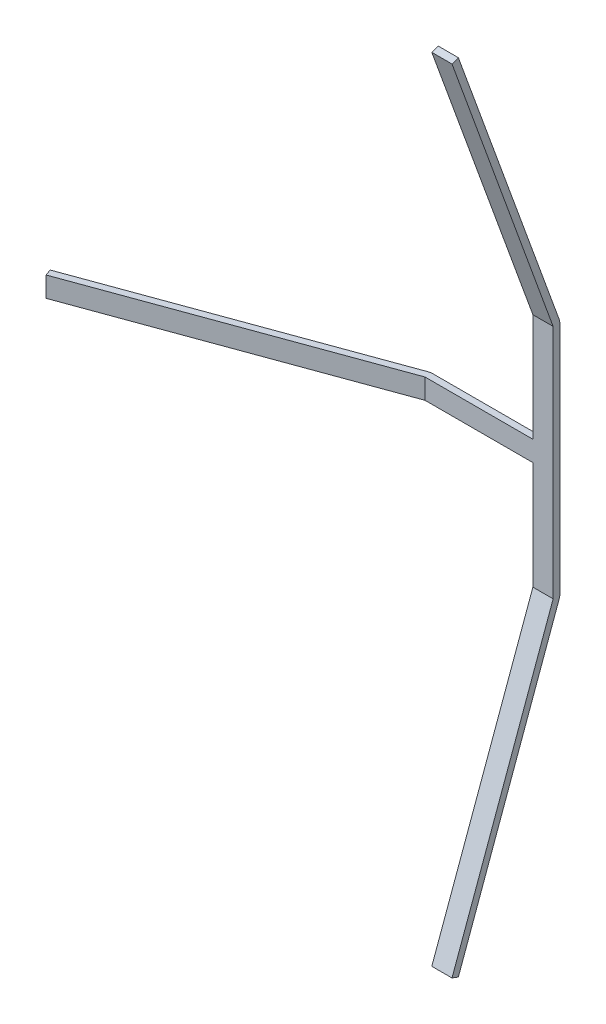
SolidWorks part; units mm, degrees
ref_plane "Front Plane" through (0, 0, 0) normal (0, 0, 1) x (1, 0, 0)
ref_plane "Top Plane" through (0, 0, 0) normal (0, 1, 0) x (1, 0, 0)
ref_plane "Right Plane" through (0, 0, 0) normal (1, 0, 0) x (0, 0, -1)
sketch "Sketch1" plane through (0, 0, 0) normal (0, 1, 0) x (1, 0, 0)
  line L0 (0, 0) -> (412.1216, 0)
  line L1 (412.1216, 0) -> (412.1216, 150)
  line L2 (412.1216, 150) -> (0, 0)
  dimension "D1" = 150
  dimension "D2" = 20
extrude "Boss-Extrude1" add sketch "Sketch1" along normal blind 350
sketch "Sketch2" plane through (412.1216, 0, 0) normal (1, 0, 0) x (0, 0, -1)
  line L4 (0, 0) -> (150, 0)
  line L5 (150, 0) -> (150, 350)
  line L6 (150, 350) -> (0, 350)
  line L7 (0, 350) -> (0, 0)
  line L8 (0, 0) -> (150, 0)
  line L9 (150, 0) -> (150, 350)
  line L10 (150, 350) -> (0, 350)
  line L11 (0, 350) -> (0, 0)
  dimension "D1" = 0
extrude "Boss-Extrude2" add sketch "Sketch2" along normal blind 350
sketch "Sketch4" plane through (762.1216, 0, 0) normal (1, 0, 0) x (0, 0, -1)
  line L0 (0, 350) -> (0, 762.1216)
  line L1 (0, 762.1216) -> (150, 350)
  line L2 (0, 350) -> (150, 350)
  line L6 (0, 350) -> (0, 0)
  line L7 (0, 0) -> (150, 0)
  line L8 (150, 0) -> (150, 350)
  line L9 (150, 350) -> (0, 350)
  line L10 (0, 350) -> (0, 0)
  line L11 (0, 0) -> (150, 0)
  line L12 (150, 0) -> (150, 350)
  line M10 (150, 350) -> (0, 350)
  dimension "D1" = 20
  dimension "D2" = 0
extrude "Boss-Extrude3" add sketch "Sketch4" against normal blind 350 contours L1 L0 M10
sketch "Sketch5" plane through (762.1216, 0, 0) normal (1, 0, 0) x (0, 0, -1)
  line L0 (0, 0) -> (0, -412.1216)
  line L1 (0, -412.1216) -> (150, 0)
  line L2 (0, 0) -> (150, 0)
  dimension "D1" = 20
extrude "Boss-Extrude4" add sketch "Sketch5" against normal blind 350
sketch "Sketch6" plane through (0, 0, 0) normal (-0.342, 0, -0.9397) x (-0.9397, 0, 0.342)
  line L0 (0, 160) -> (-438.5707, 160)
  line L1 (0, 350) -> (0, 0) construction
  line L2 (-438.5707, 350) -> (-438.5707, 0) construction
  line L3 (0, 175) -> (-124.4564, 175) construction
  line L4 (0, 190) -> (-438.5707, 190)
  line L5 (0, 190) -> (0, 160)
  line L6 (-438.5707, 190) -> (-438.5707, 160)
  dimension "D1" = 15
extrude "Cut-Extrude1" cut sketch "Sketch6" against normal blind 10
sketch "Sketch7" plane through (0, 0, -150) normal (0, 0, -1) x (-1, 0, 0)
  line L0 (-587.1216, 350) -> (-587.1216, 0) construction
  line L1 (-762.1216, 350) -> (-412.1216, 350) construction
  line L2 (-762.1216, 0) -> (-412.1216, 0) construction
  line L3 (-415.5418, 175) -> (-762.1216, 175) construction
  line L4 (-415.5418, 190) -> (-415.5418, 160) construction
  line L5 (-762.1216, 0) -> (-762.1216, 350) construction
  line L6 (-412.1216, 190) -> (-572.1216, 190)
  line L7 (-572.1216, 190) -> (-572.1216, 350)
  line L8 (-412.1216, 160) -> (-572.1216, 160)
  line L9 (-572.1216, 160) -> (-572.1216, 0)
  line L10 (-602.1216, 160) -> (-602.1216, 0)
  line L11 (-602.1216, 190) -> (-602.1216, 350)
  line L12 (-602.1216, 190) -> (-602.1216, 164.9009)
  line L13 (-602.1216, 0) -> (-572.1216, 0)
  line L14 (-602.1216, 350) -> (-572.1216, 350)
  line L15 (-412.1216, 160) -> (-412.1216, 190)
  line L16 (-602.1216, 164.9009) -> (-602.1216, 160)
  dimension "D1" = 15
extrude "Cut-Extrude2" cut sketch "Sketch7" against normal blind 10
sketch "Sketch8" plane through (0, -48.2091, -132.4533) normal (0, -0.342, -0.9397) x (-1, 0, 0)
  line L0 (-602.1216, 51.303) -> (-602.1216, -387.2676)
  line L1 (-412.1216, -387.2676) -> (-762.1216, -387.2676) construction
  line L2 (-572.1216, 51.303) -> (-572.1216, -387.2676)
  line L3 (-572.1216, -387.2676) -> (-602.1216, -387.2676)
  line L4 (-602.1216, 51.303) -> (-572.1216, 51.303)
extrude "Cut-Extrude3" cut sketch "Sketch8" against normal blind 10
sketch "Sketch9" plane through (0, 89.1513, -244.9412) normal (0, 0.342, -0.9397) x (-1, 0, 0)
  line L0 (-602.1216, 277.5894) -> (-602.1216, 716.1601)
  line L1 (-412.1216, 716.1601) -> (-762.1216, 716.1601) construction
  line L2 (-572.1216, 277.5894) -> (-572.1216, 716.1601)
  line L3 (-572.1216, 716.1601) -> (-602.1216, 716.1601)
  line L4 (-602.1216, 277.5894) -> (-572.1216, 277.5894)
extrude "Cut-Extrude4" cut sketch "Sketch9" against normal blind 10
sketch "Sketch12" plane through (0, 0, 0) normal (-0.342, 0, -0.9397) x (-0.9397, 0, 0.342)
  line L0 (0, 190) -> (-438.5707, 190) construction
  line L1 (-438.5707, 160) -> (0, 160) construction
  line L2 (0, 190) -> (-438.5707, 190)
  line L3 (-438.5707, 160) -> (0, 160)
  line L4 (0, 160) -> (0, 190)
  line L5 (-438.5707, 160) -> (-438.5707, 190)
extrude "Boss-Extrude5" add sketch "Sketch12" along normal blind 10 separate body
sketch "Sketch13" plane through (0, 0, -150) normal (0, 0, -1) x (-1, 0, 0)
  line L0 (-572.1216, 0) -> (-572.1216, 160) construction
  line L1 (-602.1216, 350) -> (-602.1216, 0) construction
  line L2 (-572.1216, 190) -> (-572.1216, 350) construction
  line L3 (-412.1216, 190) -> (-572.1216, 190) construction
  line L4 (-572.1216, 160) -> (-412.1216, 160) construction
  line L5 (-572.1216, 0) -> (-572.1216, 160)
  line L6 (-602.1216, 350) -> (-602.1216, 0)
  line L7 (-572.1216, 190) -> (-572.1216, 350)
  line L8 (-412.1216, 190) -> (-572.1216, 190)
  line L9 (-572.1216, 160) -> (-412.1216, 160)
  line L10 (-602.1216, 0) -> (-572.1216, 0)
  line L11 (-412.1216, 190) -> (-412.1216, 160)
  line L12 (-602.1216, 350) -> (-572.1216, 350)
extrude "Boss-Extrude6" add sketch "Sketch13" along normal blind 10 separate body
sketch "Sketch14" plane through (0, -48.2091, -132.4533) normal (0, -0.342, -0.9397) x (-1, 0, 0)
  line L0 (-602.1216, 51.303) -> (-602.1216, -387.2676) construction
  line L1 (-572.1216, -387.2676) -> (-572.1216, 51.303) construction
  line L2 (-602.1216, 51.303) -> (-602.1216, -387.2676)
  line L3 (-572.1216, -387.2676) -> (-572.1216, 51.303)
  line L4 (-602.1216, 51.303) -> (-572.1216, 51.303)
  line L5 (-602.1216, -387.2676) -> (-572.1216, -387.2676)
extrude "Boss-Extrude7" add sketch "Sketch14" along normal blind 10 separate body
sketch "Sketch15" plane through (0, 89.1513, -244.9412) normal (0, 0.342, -0.9397) x (-1, 0, 0)
  line L0 (-602.1216, 716.1601) -> (-602.1216, 277.5894) construction
  line L1 (-572.1216, 277.5894) -> (-572.1216, 716.1601) construction
  line L2 (-602.1216, 716.1601) -> (-602.1216, 277.5894)
  line L3 (-572.1216, 277.5894) -> (-572.1216, 716.1601)
  line L4 (-572.1216, 277.5894) -> (-602.1216, 277.5894)
  line L6 (-572.1216, 716.1601) -> (-602.1216, 716.1601)
extrude "Boss-Extrude8" add sketch "Sketch15" along normal blind 10 separate body
sketch "Sketch17" plane through (602.1216, 0, 0) normal (1, 0, 0) x (0, 0, -1)
  line L0 (160, 350) -> (159.3969, 353.4202)
  line L1 (159.3969, 353.4202) -> (150, 350)
  line L2 (150, 350) -> (160, 350)
extrude "Boss-Extrude10" add sketch "Sketch17" against normal up to surface (30 mm away) up to face at (572.1216, 270, -155)
sketch "Sketch18" plane through (602.1216, 0, 0) normal (1, 0, 0) x (0, 0, -1)
  line L0 (159.3969, -3.4202) -> (150, 0)
  line L1 (150, 0) -> (160, 0)
  line L2 (160, 0) -> (159.3969, -3.4202)
extrude "Boss-Extrude11" add sketch "Sketch18" against normal up to surface (30 mm away) up to face at (572.1216, -207.7709, -79.6985)
sketch "Sketch19" plane through (0, 160, 0) normal (0, -1, 0) x (1, 0, 0)
  line L0 (408.7014, -159.3969) -> (412.1216, -150)
  line L1 (412.1216, -150) -> (412.1216, -160)
  line L2 (412.1216, -160) -> (408.7014, -159.3969)
extrude "Boss-Extrude12" add sketch "Sketch19" against normal up to surface (30 mm away) up to face at (204.3507, 190, -79.6985)
sketch "Sketch20" plane through (0, 0, 0) normal (-0.342, 0, -0.9397) x (-0.9397, 0, 0.342)
  line L4 (0, 0) -> (0, 160)
  line L5 (0, 160) -> (-438.5707, 160)
  line L6 (-438.5707, 160) -> (-438.5707, 0)
  line L7 (-438.5707, 0) -> (0, 0)
  line L8 (0, 0) -> (0, 160)
  line L9 (0, 160) -> (-438.5707, 160)
  line L10 (-438.5707, 160) -> (-438.5707, 0)
  line L11 (-438.5707, 0) -> (0, 0)
  dimension "D1" = 0
extrude "Cut-Extrude5" cut sketch "Sketch20" against normal blind 1000
sketch "Sketch21" plane through (0, 0, 0) normal (-0.342, 0, -0.9397) x (-0.9397, 0, 0.342)
  line L4 (-438.5707, 350) -> (-438.5707, 190)
  line L5 (-438.5707, 190) -> (0, 190)
  line L6 (0, 190) -> (0, 350)
  line L7 (0, 350) -> (-438.5707, 350)
  line L8 (-438.5707, 350) -> (-438.5707, 190)
  line L9 (-438.5707, 190) -> (0, 190)
  line L10 (0, 190) -> (0, 350)
  line L11 (0, 350) -> (-438.5707, 350)
  dimension "D1" = 0
extrude "Cut-Extrude6" cut sketch "Sketch21" against normal blind 1000
sketch "Sketch22" plane through (0, 0, -150) normal (0, 0, -1) x (-1, 0, 0)
  line L4 (-412.1216, 350) -> (-572.1216, 350)
  line L5 (-572.1216, 350) -> (-572.1216, 190)
  line L6 (-572.1216, 190) -> (-412.1216, 190)
  line L7 (-412.1216, 190) -> (-412.1216, 350)
  line L8 (-412.1216, 350) -> (-572.1216, 350)
  line L9 (-572.1216, 350) -> (-572.1216, 190)
  line L10 (-572.1216, 190) -> (-412.1216, 190)
  line L11 (-412.1216, 190) -> (-412.1216, 350)
  dimension "D1" = 0
extrude "Cut-Extrude7" cut sketch "Sketch22" against normal blind 1000
sketch "Sketch23" plane through (0, 0, -150) normal (0, 0, -1) x (-1, 0, 0)
  line L4 (-412.1216, 0) -> (-412.1216, 160)
  line L5 (-412.1216, 160) -> (-572.1216, 160)
  line L6 (-572.1216, 160) -> (-572.1216, 0)
  line L7 (-572.1216, 0) -> (-412.1216, 0)
  line L8 (-412.1216, 0) -> (-412.1216, 160)
  line L9 (-412.1216, 160) -> (-572.1216, 160)
  line L10 (-572.1216, 160) -> (-572.1216, 0)
  line L11 (-572.1216, 0) -> (-412.1216, 0)
  dimension "D1" = 0
extrude "Cut-Extrude8" cut sketch "Sketch23" against normal blind 1000
sketch "Sketch24" plane through (0, -48.2091, -132.4533) normal (0, -0.342, -0.9397) x (-1, 0, 0)
  line L4 (-572.1216, 51.303) -> (-572.1216, -387.2676)
  line L5 (-572.1216, -387.2676) -> (-412.1216, -387.2676)
  line L6 (-412.1216, -387.2676) -> (-412.1216, 51.303)
  line L7 (-412.1216, 51.303) -> (-572.1216, 51.303)
  line L8 (-572.1216, 51.303) -> (-572.1216, -387.2676)
  line L9 (-572.1216, -387.2676) -> (-412.1216, -387.2676)
  line L10 (-412.1216, -387.2676) -> (-412.1216, 51.303)
  line L11 (-412.1216, 51.303) -> (-572.1216, 51.303)
  dimension "D1" = 0
extrude "Cut-Extrude9" cut sketch "Sketch24" against normal blind 1000
sketch "Sketch25" plane through (0, -48.2091, -132.4533) normal (0, -0.342, -0.9397) x (-1, 0, 0)
  line L4 (-602.1216, -387.2676) -> (-602.1216, 51.303)
  line L5 (-602.1216, 51.303) -> (-762.1216, 51.303)
  line L6 (-762.1216, 51.303) -> (-762.1216, -387.2676)
  line L7 (-762.1216, -387.2676) -> (-602.1216, -387.2676)
  line L8 (-602.1216, -387.2676) -> (-602.1216, 51.303)
  line L9 (-602.1216, 51.303) -> (-762.1216, 51.303)
  line L10 (-762.1216, 51.303) -> (-762.1216, -387.2676)
  line L11 (-762.1216, -387.2676) -> (-602.1216, -387.2676)
  dimension "D1" = 0
extrude "Cut-Extrude10" cut sketch "Sketch25" against normal blind 1000
sketch "Sketch26" plane through (0, 0, -150) normal (0, 0, -1) x (-1, 0, 0)
  line L4 (-762.1216, 0) -> (-602.1216, 0)
  line L5 (-602.1216, 0) -> (-602.1216, 350)
  line L6 (-602.1216, 350) -> (-762.1216, 350)
  line L7 (-762.1216, 350) -> (-762.1216, 0)
  line L8 (-762.1216, 0) -> (-602.1216, 0)
  line L9 (-602.1216, 0) -> (-602.1216, 350)
  line L10 (-602.1216, 350) -> (-762.1216, 350)
  line L11 (-762.1216, 350) -> (-762.1216, 0)
  dimension "D1" = 0
extrude "Cut-Extrude11" cut sketch "Sketch26" against normal blind 1000
sketch "Sketch27" plane through (0, 89.1513, -244.9412) normal (0, 0.342, -0.9397) x (-1, 0, 0)
  line L4 (-762.1216, 277.5894) -> (-602.1216, 277.5894)
  line L5 (-602.1216, 277.5894) -> (-602.1216, 716.1601)
  line L6 (-602.1216, 716.1601) -> (-762.1216, 716.1601)
  line L7 (-762.1216, 716.1601) -> (-762.1216, 277.5894)
  line L8 (-762.1216, 277.5894) -> (-602.1216, 277.5894)
  line L9 (-602.1216, 277.5894) -> (-602.1216, 716.1601)
  line L10 (-602.1216, 716.1601) -> (-762.1216, 716.1601)
  line L11 (-762.1216, 716.1601) -> (-762.1216, 277.5894)
  dimension "D1" = 0
extrude "Cut-Extrude12" cut sketch "Sketch27" against normal blind 1000
sketch "Sketch28" plane through (0, 89.1513, -244.9412) normal (0, 0.342, -0.9397) x (-1, 0, 0)
  line L4 (-412.1216, 716.1601) -> (-572.1216, 716.1601)
  line L5 (-572.1216, 716.1601) -> (-572.1216, 277.5894)
  line L6 (-572.1216, 277.5894) -> (-412.1216, 277.5894)
  line L7 (-412.1216, 277.5894) -> (-412.1216, 716.1601)
  line L8 (-412.1216, 716.1601) -> (-572.1216, 716.1601)
  line L9 (-572.1216, 716.1601) -> (-572.1216, 277.5894)
  line L10 (-572.1216, 277.5894) -> (-412.1216, 277.5894)
  line L11 (-412.1216, 277.5894) -> (-412.1216, 716.1601)
  dimension "D1" = 0
extrude "Cut-Extrude13" cut sketch "Sketch28" against normal blind 1000
sketch "Sketch29" plane through (0, 160, 0) normal (0, -1, 0) x (1, 0, 0)
  line L4 (572.1216, 0) -> (29.238, 0)
  line L5 (29.238, 0) -> (413.8849, -140)
  line L6 (413.8849, -140) -> (572.1216, -140)
  line L7 (572.1216, -140) -> (572.1216, 0)
  line L8 (572.1216, 0) -> (29.238, 0)
  line L9 (29.238, 0) -> (413.8849, -140)
  line L10 (413.8849, -140) -> (572.1216, -140)
  line L11 (572.1216, -140) -> (572.1216, 0)
  dimension "D1" = 0
extrude "Cut-Extrude14" cut sketch "Sketch29" against normal blind 1000
sketch "Sketch30" plane through (572.1216, 0, 0) normal (-1, 0, 0) x (0, 0, 1)
  line L4 (-140, 348.2367) -> (-140, 1.7633)
  line L5 (-140, 1.7633) -> (0, -382.8836)
  line L6 (0, -382.8836) -> (0, 732.8836)
  line L7 (0, 732.8836) -> (-140, 348.2367)
  line L8 (-140, 348.2367) -> (-140, 1.7633)
  line L9 (-140, 1.7633) -> (0, -382.8836)
  line L10 (0, -382.8836) -> (0, 732.8836)
  line L11 (0, 732.8836) -> (-140, 348.2367)
  dimension "D1" = 0
extrude "Cut-Extrude15" cut sketch "Sketch30" against normal blind 1000
